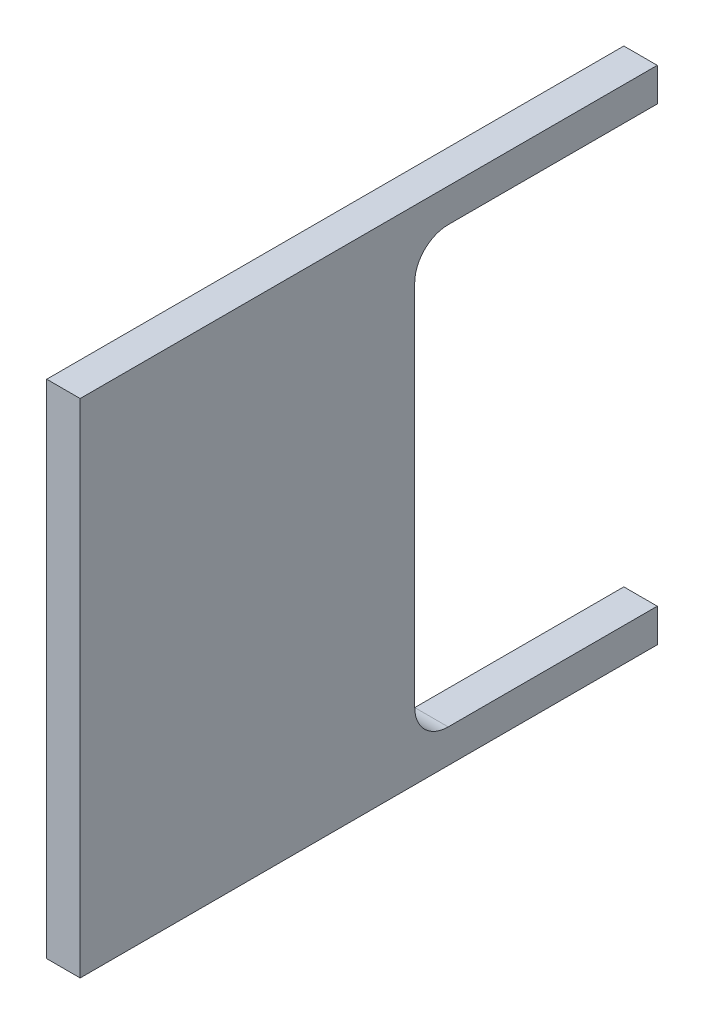
SolidWorks part; units mm, degrees
material "MDF"
ref_plane "Front Plane" through (0, 0, 0) normal (0, 0, 1) x (1, 0, 0)
ref_plane "Top Plane" through (0, 0, 0) normal (0, 1, 0) x (1, 0, 0)
ref_plane "Right Plane" through (0, 0, 0) normal (1, 0, 0) x (0, 0, -1)
sketch "Sketch1" plane through (0, 0, 0) normal (1, 0, 0) x (0, 0, -1)
  line L1 (-109.5375, -95.25) -> (109.5375, -95.25)
  line L2 (-109.5375, -95.25) -> (-109.5375, 95.25)
  line L3 (-109.5375, 95.25) -> (109.5375, 95.25)
  line L4 (109.5375, -95.25) -> (109.5375, 95.25)
  line L5 (-109.5375, -95.25) -> (109.5375, 95.25) construction
  line L6 (-109.5375, 95.25) -> (109.5375, -95.25) construction
  point P0 (0, 0)
  dimension "D1" = 219.075
  dimension "D2" = 190.5
extrude "Boss-Extrude1" add sketch "Sketch1" along normal blind 12.7
sketch "Sketch2" plane through (12.7, 0, 0) normal (1, 0, 0) x (0, 0, -1)
  line L0 (109.5375, -95.25) -> (109.5375, 95.25) construction
  line L1 (109.5375, 82.55) -> (17.4625, 82.55)
  line L2 (109.5375, 82.55) -> (109.5375, -82.55)
  line L3 (109.5375, -82.55) -> (17.4625, -82.55)
  line L4 (17.4625, 82.55) -> (17.4625, -82.55)
  line L5 (0, 0) -> (171.8543, 0) construction
  line L6 (6.985, 0) -> (-6.985, 0) construction
  dimension "D1" = 165.1
  dimension "D2" = 92.075
extrude "Cut-Extrude1" cut sketch "Sketch2" against normal up to next
fillet "Fillet1" radius 12.7 2 edges at (6.35, -82.55, -17.4625) (6.35, 82.55, -17.4625)
